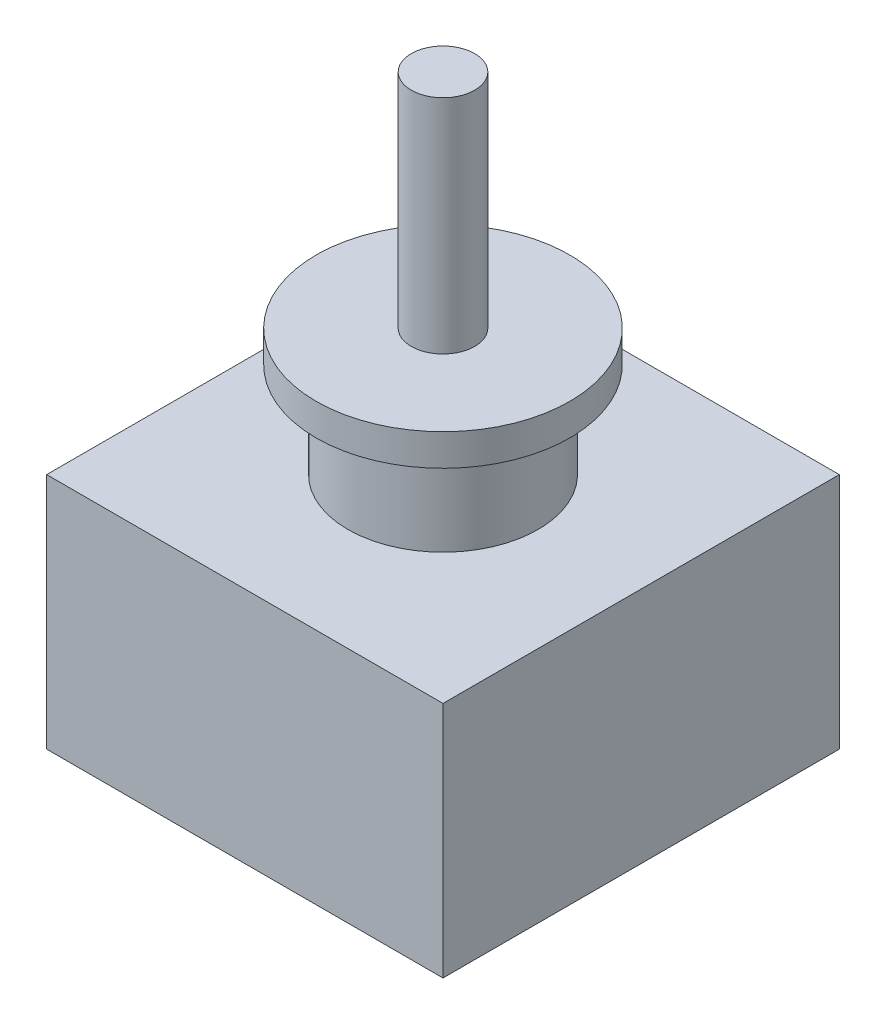
SolidWorks part; units mm, degrees
material "ABS"
ref_plane "Plan de face" through (0, 0, 0) normal (0, 0, 1) x (1, 0, 0)
ref_plane "Plan de dessus" through (0, 0, 0) normal (0, 1, 0) x (1, 0, 0)
ref_plane "Plan de droite" through (0, 0, 0) normal (1, 0, 0) x (0, 0, -1)
sketch "Esquisse1" plane through (0, 0, 0) normal (0, 1, 0) x (1, 0, 0)
  line L0 (12.5, -12.5) -> (-12.5, 12.5) construction
  line L1 (-12.5, -12.5) -> (12.5, -12.5)
  line L2 (-12.5, -12.5) -> (-12.5, 12.5)
  line L3 (-12.5, 12.5) -> (12.5, 12.5)
  line L4 (12.5, -12.5) -> (12.5, 12.5)
  dimension "D1" = 25
  dimension "D2" = 25
extrude "Extrusion1" add sketch "Esquisse1" along normal blind 15
sketch "Esquisse2" plane through (0, 15, 0) normal (0, 1, 0) x (-1, 0, 0)
  line L0 (12.5, 0) -> (-12.5, 0) construction
  line L1 (12.5, -12.5) -> (12.5, 12.5) construction
  line L2 (-12.5, 12.5) -> (-12.5, -12.5) construction
  circle A0 centre (0, 0) radius 6
  dimension "D1" = 12
extrude "Extrusion2" add sketch "Esquisse2" along normal blind 6
sketch "Esquisse3" plane through (0, 21, 0) normal (0, 1, 0) x (-1, 0, 0)
  circle A0 centre (0, 0) radius 8
  circle A1 centre (0, 0) radius 6 construction
  dimension "D1" = 16
extrude "Extrusion3" add sketch "Esquisse3" along normal blind 2
sketch "Esquisse4" plane through (0, 23, 0) normal (0, 1, 0) x (-1, 0, 0)
  circle A0 centre (0, 0) radius 2
  circle A1 centre (0, 0) radius 8 construction
  dimension "D1" = 4
extrude "Extrusion4" add sketch "Esquisse4" along normal blind 14
